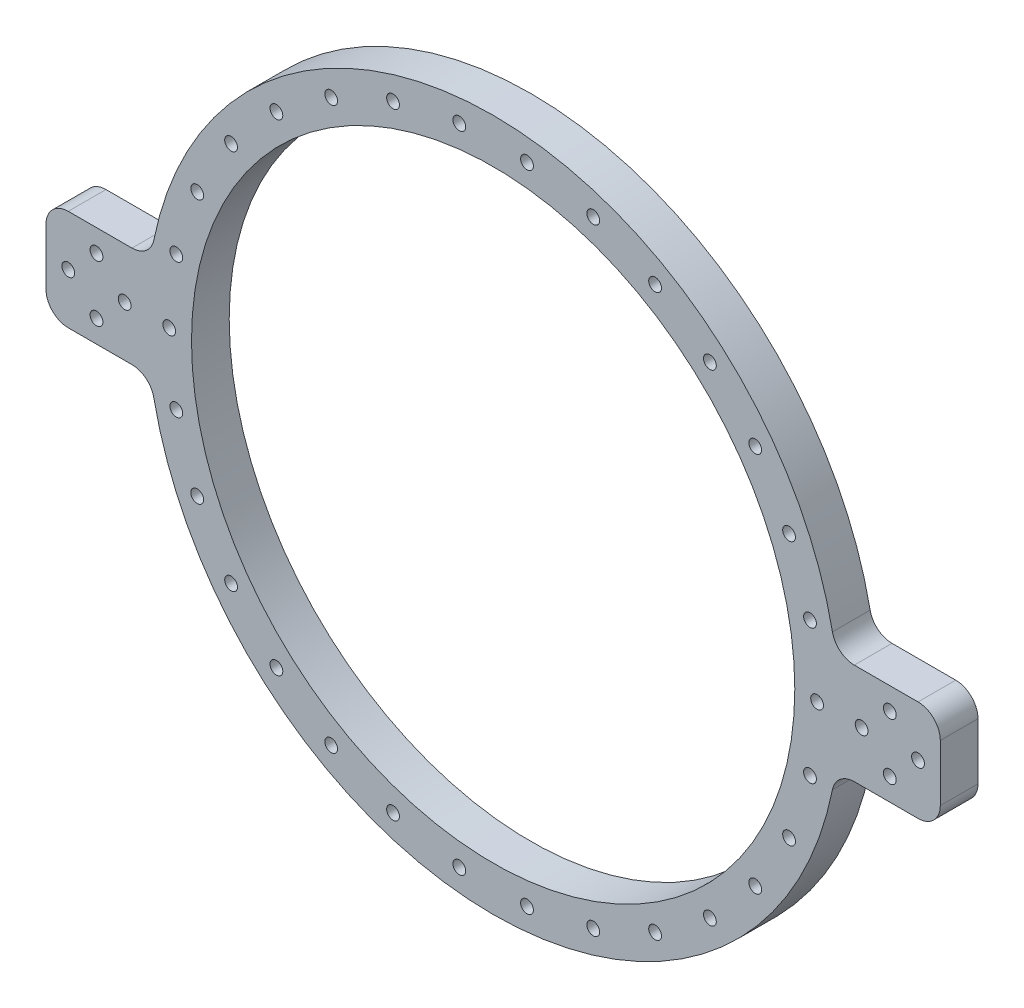
SolidWorks part; units mm, degrees
material "PC High Viscosity"
ref_plane "Front Plane" through (0, 0, 0) normal (0, 0, 1) x (1, 0, 0)
ref_plane "Top Plane" through (0, 0, 0) normal (0, 1, 0) x (1, 0, 0)
ref_plane "Right Plane" through (0, 0, 0) normal (1, 0, 0) x (0, 0, -1)
sketch "Sketch1" plane through (0, 0, 0) normal (0, 0, 1) x (1, 0, 0)
  line L0 (109.1, 0) -> (101.6, 0) construction
  line L1 (109.1, 0) -> (116.6, 0) construction
  line L2 (115.3265, 17) -> (143.1, 17)
  line L3 (150.6, 9.5) -> (150.6, -9.5)
  line L4 (143.1, -17) -> (115.3265, -17)
  line L5 (0, 0) -> (204.7679, 0) construction
  line L6 (0, 0) -> (0, 58.5097) construction
  line L7 (133.6, 9.5) -> (143.1, 0) construction
  line L8 (143.1, 0) -> (133.6, -9.5) construction
  line L9 (133.6, -9.5) -> (124.1, 0) construction
  line L10 (124.1, 0) -> (133.6, 9.5) construction
  line L11 (133.6, 9.5) -> (133.6, 17) construction
  line L12 (124.1, 0) -> (116.6, 0) construction
  line L13 (-115.3265, 17) -> (-143.1, 17)
  line L14 (-150.6, 9.5) -> (-150.6, -9.5)
  line L15 (-143.1, -17) -> (-115.3265, -17)
  circle A0 centre (0, 0) radius 101.6
  arc A1 (115.3265, 17) -> (-115.3265, 17) centre (0, 0) ccw
  circle A2 centre (109.1, 0) radius 2.1525
  circle A4 centre (106.7159, -22.6832) radius 2.1525
  circle A5 centre (99.6678, -44.375) radius 2.1525
  circle A6 centre (88.2638, -64.1274) radius 2.1525
  circle A7 centre (73.0021, -81.0771) radius 2.1525
  circle A8 centre (54.55, -94.4834) radius 2.1525
  circle A9 centre (33.7138, -103.7603) radius 2.1525
  circle A10 centre (11.4041, -108.5023) radius 2.1525
  circle A11 centre (-11.4041, -108.5023) radius 2.1525
  circle A12 centre (-33.7138, -103.7603) radius 2.1525
  circle A13 centre (-54.55, -94.4834) radius 2.1525
  circle A14 centre (-73.0021, -81.0771) radius 2.1525
  circle A15 centre (-88.2638, -64.1274) radius 2.1525
  circle A16 centre (-99.6678, -44.375) radius 2.1525
  circle A17 centre (-106.7159, -22.6832) radius 2.1525
  circle A18 centre (-109.1, 0) radius 2.1525
  circle A19 centre (-106.7159, 22.6832) radius 2.1525
  circle A20 centre (-99.6678, 44.375) radius 2.1525
  circle A21 centre (-88.2638, 64.1274) radius 2.1525
  circle A22 centre (-73.0021, 81.0771) radius 2.1525
  circle A23 centre (-54.55, 94.4834) radius 2.1525
  circle A24 centre (-33.7138, 103.7603) radius 2.1525
  circle A25 centre (-11.4041, 108.5023) radius 2.1525
  circle A26 centre (11.4041, 108.5023) radius 2.1525
  circle A27 centre (33.7138, 103.7603) radius 2.1525
  circle A28 centre (54.55, 94.4834) radius 2.1525
  circle A29 centre (73.0021, 81.0771) radius 2.1525
  circle A30 centre (88.2638, 64.1274) radius 2.1525
  circle A31 centre (99.6678, 44.375) radius 2.1525
  circle A32 centre (106.7159, 22.6832) radius 2.1525
  arc A33 (143.1, 17) -> (150.6, 9.5) centre (143.1, 9.5) cw
  arc A34 (150.6, -9.5) -> (143.1, -17) centre (143.1, -9.5) cw
  circle A35 centre (133.6, 9.5) radius 2.1525
  circle A36 centre (133.6, -9.5) radius 2.1525
  circle A37 centre (143.1, 0) radius 2.1525
  circle A38 centre (124.1, 0) radius 2.1525
  arc A39 (115.3265, -17) -> (116.5727, 0) centre (0, 0) ccw construction
  arc A40 (-143.1, 17) -> (-150.6, 9.5) centre (-143.1, 9.5) ccw
  arc A41 (-150.6, -9.5) -> (-143.1, -17) centre (-143.1, -9.5) ccw
  circle A42 centre (-143.1, 0) radius 2.1525
  circle A43 centre (-133.6, -9.5) radius 2.1525
  circle A44 centre (-124.1, 0) radius 2.1525
  circle A45 centre (-133.6, 9.5) radius 2.1525
  arc A46 (-115.3265, -17) -> (115.3265, -17) centre (0, 0) ccw
  dimension "D1" = 203.2
  dimension "D2" = 30
  dimension "D3" = 4.305
  dimension "D6" = 19
  dimension "D7" = 4.305
  dimension "D11" = 7.5
  dimension "D13" = 116.5727
  dimension "D14" = 109.1
  dimension "D4" = 7.5
  dimension "D5" = 7.5
  dimension "D8" = 19
  dimension "D9" = 7.5
  dimension "D10" = 7.5
  dimension "D12" = 7.5
  dimension "D15" = 22.8081
extrude "Boss-Extrude1" add sketch "Sketch1" along normal blind 12.7
fillet "Fillet1" radius 7.5 4 edges at (115.3265, -17, 6.35) (115.3265, 17, 6.35) (-115.3265, -17, 6.35) (-115.3265, 17, 6.35)
